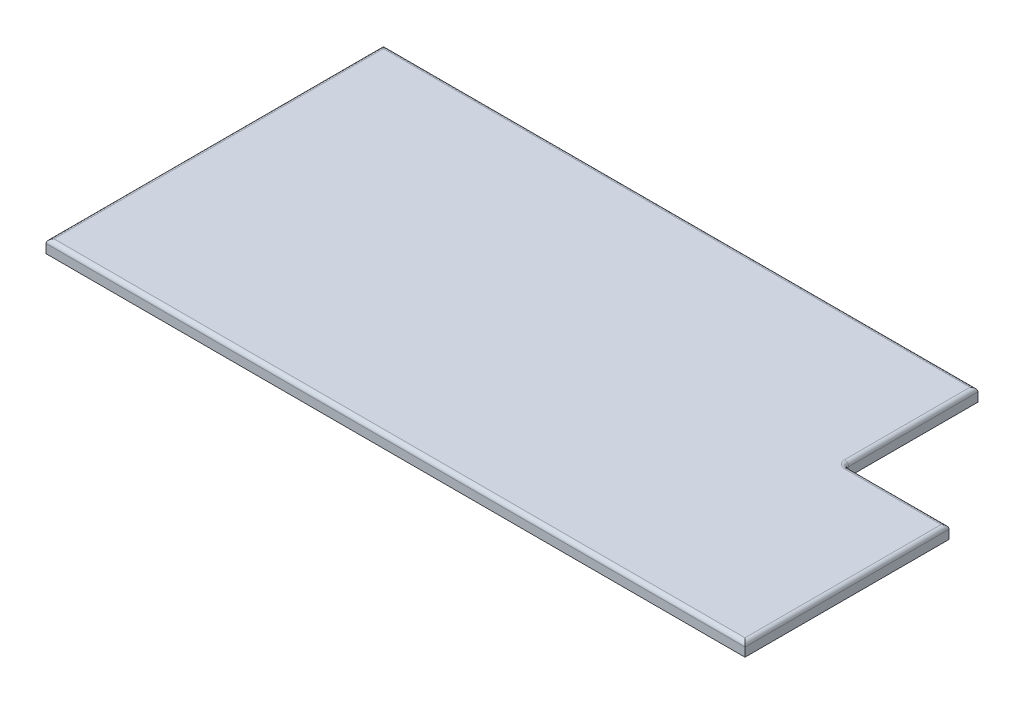
SolidWorks part; units mm, degrees
material "PET"
ref_plane "Спереди" through (0, 0, 0) normal (0, 0, 1) x (1, 0, 0)
ref_plane "Сверху" through (0, 0, 0) normal (0, 1, 0) x (1, 0, 0)
ref_plane "Справа" through (0, 0, 0) normal (1, 0, 0) x (0, 0, -1)
other "Configuration Table"
sketch "Эскиз55" plane through (0, 0, 0) normal (0, 1, 0) x (1, 0, 0)
  line L1 (0, 0) -> (87, 0)
  line L2 (0, 0) -> (0, 42)
  line L3 (0, 42) -> (87, 42)
  line L4 (87, 0) -> (87, 42)
  dimension "D1" = 42
  dimension "D2" = 87
extrude "Бобышка-Вытянуть1" add sketch "Эскиз55" along normal blind 1.6
sketch "Эскиз56" plane through (0, 1.6, 0) normal (0, 1, 0) x (1, 0, 0)
  line L1 (87, 42) -> (74, 42)
  line L2 (87, 42) -> (87, 25.4)
  line L3 (87, 25.4) -> (74, 25.4)
  line L4 (74, 42) -> (74, 25.4)
  dimension "D1" = 16.6
  dimension "D2" = 13
extrude "Вырез-Вытянуть1" cut sketch "Эскиз56" against normal blind 1.6
fillet "Скругление1" radius 0.5 7 edges at (43.5, 1.6, 0) (0, 1.6, -21) (37, 1.6, -42) (74, 1.6, -33.7) (80.5, 1.6, -25.4) (87, 1.6, -12.7) (74, 0.8, -25.4)
